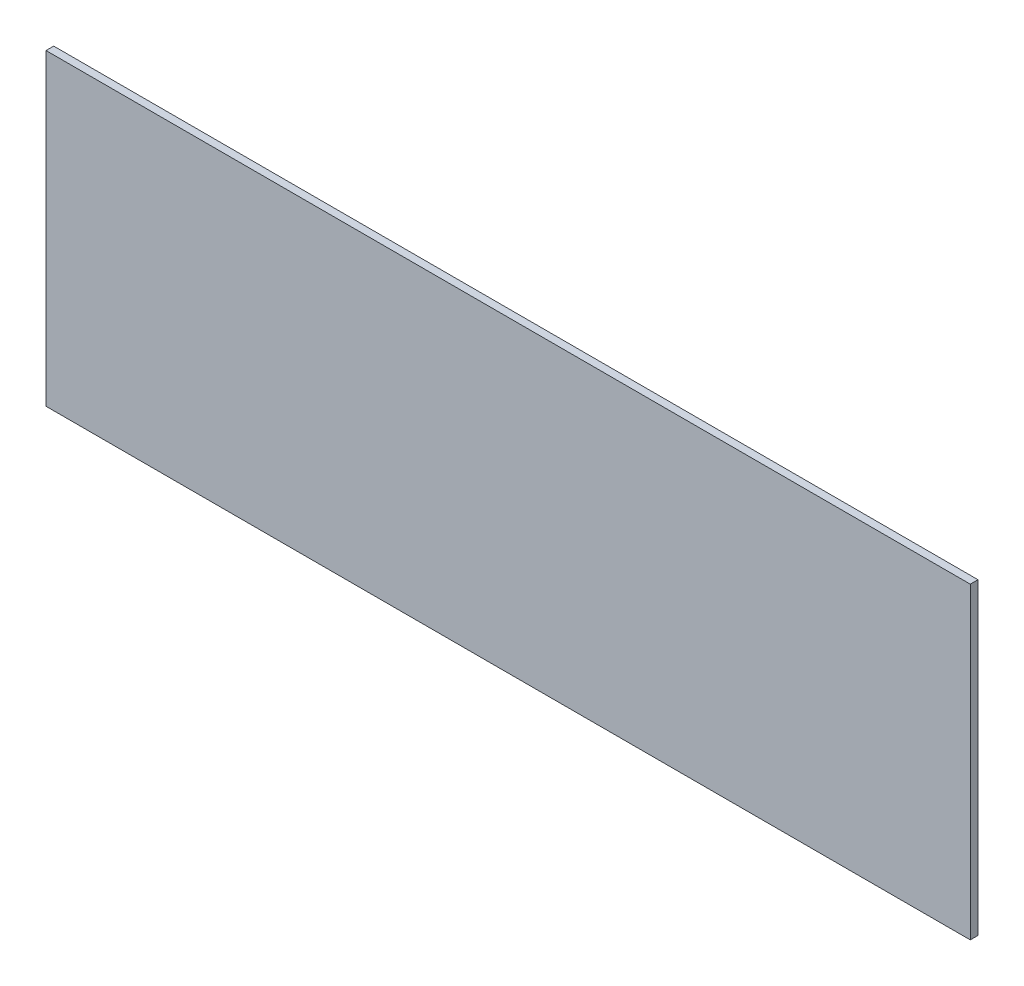
SolidWorks part; units mm, degrees
ref_plane "前视基准面" through (0, 0, 0) normal (0, 0, 1) x (1, 0, 0)
ref_plane "上视基准面" through (0, 0, 0) normal (0, 1, 0) x (1, 0, 0)
ref_plane "右视基准面" through (0, 0, 0) normal (1, 0, 0) x (0, 0, -1)
sketch "草图1" plane through (0, 0, 0) normal (0, 0, 1) x (1, 0, 0)
  line L1 (-6000, 2000) -> (6000, 2000)
  line L2 (-6000, 2000) -> (-6000, -2000)
  line L3 (-6000, -2000) -> (6000, -2000)
  line L4 (6000, 2000) -> (6000, -2000)
  line L5 (0, -2000) -> (0, 2000) construction
  line L6 (-6000, 0) -> (6000, 0) construction
  point P1 (0, 0)
  dimension "D1" = 12000
  dimension "D2" = 4000
extrude "凸台-拉伸1" add sketch "草图1" along normal blind 100
